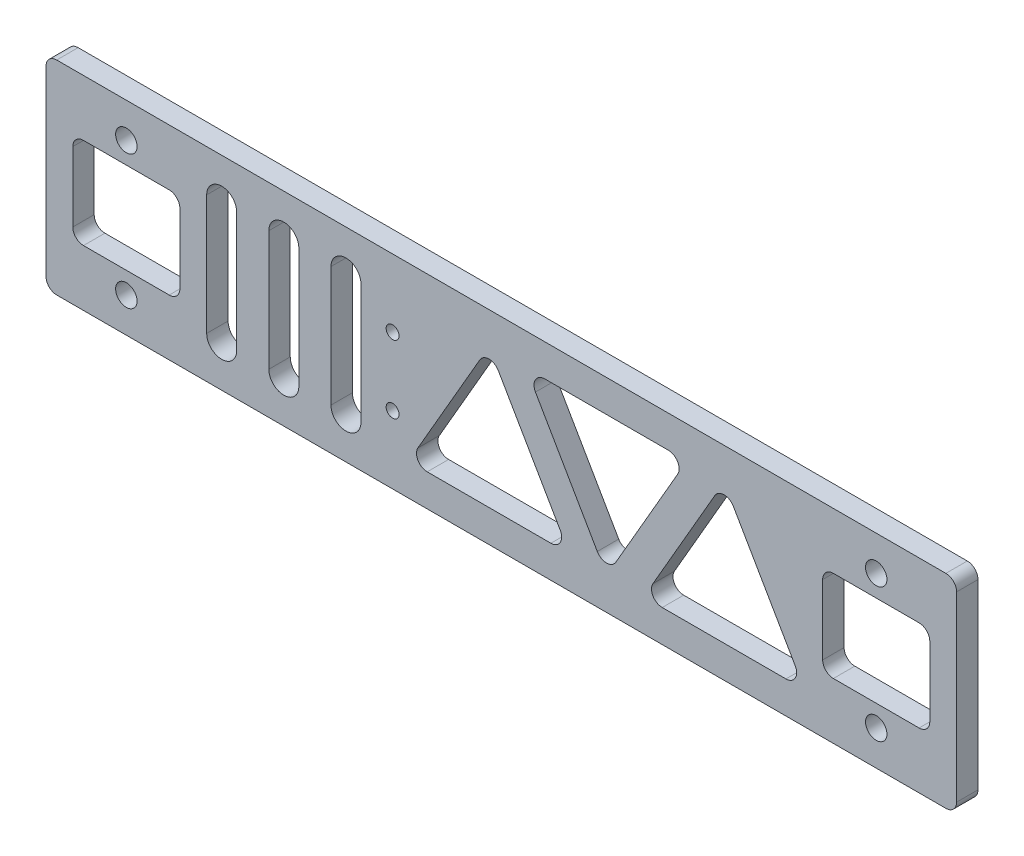
SolidWorks part; units mm, degrees
material "Thornel Mat VMA"
ref_plane "前视基准面" through (0, 0, 0) normal (0, 0, 1) x (1, 0, 0)
ref_plane "上视基准面" through (0, 0, 0) normal (0, 1, 0) x (1, 0, 0)
ref_plane "右视基准面" through (0, 0, 0) normal (1, 0, 0) x (0, 0, -1)
sketch "草图1" plane through (0, 0, 0) normal (0, 0, 1) x (1, 0, 0)
  line L1 (-85, -19) -> (85, -19)
  line L2 (-85, -19) -> (-85, 19)
  line L3 (-85, 19) -> (85, 19)
  line L4 (85, -19) -> (85, 19)
  line L5 (0, 19) -> (0, -19) construction
  line L6 (-85, 0) -> (85, 0) construction
  point P0 (0, 0)
  dimension "D1" = 170
  dimension "D2" = 38
extrude "凸台-拉伸1" add sketch "草图1" along normal blind 4
sketch "草图2" plane through (0, 0, 4) normal (0, 0, 1) x (1, 0, 0)
  line L0 (70, 19) -> (70, -19) construction
  line L1 (85, 19) -> (-85, 19) construction
  line L2 (-85, -19) -> (85, -19) construction
  line L3 (85, -19) -> (85, 19) construction
  line L4 (0, 0) -> (70, 0) construction
  circle A0 centre (70, 12.5) radius 2
  circle A1 centre (70, -12.5) radius 2
  dimension "D2" = 4
  dimension "D1" = 15
  dimension "D3" = 25
extrude "切除-拉伸1" cut sketch "草图2" against normal blind 4
mirror "镜向1" about plane through (0, 0, 0) normal (1, 0, 0) of "切除-拉伸1"
sketch "草图3" plane through (0, 0, 4) normal (0, 0, 1) x (1, 0, 0)
  line L0 (-17.295, -281.55) -> (-17.295, 41) construction
  line L1 (-17.295, -19) -> (-17.295, 19) construction
  line L2 (23.295, -281.55) -> (23.295, 41)
  line L3 (-23.295, 41) -> (-23.295, -281.55)
  line L5 (-23.295, 19) -> (-23.295, -19) construction
  line L6 (-23.295, 19) -> (-17.295, 19) construction
  line L7 (85, 19) -> (-85, 19) construction
  line L8 (-23.295, -19) -> (-17.295, -19) construction
  line L9 (-85, -19) -> (85, -19) construction
  line L10 (-20.295, 19) -> (-20.295, -19) construction
  line L11 (0, 0) -> (-20.295, 0) construction
  circle A0 centre (-20.295, 6.35) radius 1.2
  circle A1 centre (-20.295, -6.35) radius 1.2
  arc A2 (-23.295, -281.55) -> (23.295, -281.55) centre (0, -281.55) ccw
  arc A3 (23.295, 41) -> (-23.295, 41) centre (0, 41) ccw
  dimension "D2" = 2.4
  dimension "D3" = 12.7
  dimension "D1" = 0
extrude "切除-拉伸2" cut sketch "草图3" against normal blind 10
sketch "草图4" plane through (0, 0, 4) normal (0, 0, 1) x (1, 0, 0)
  line L0 (-70, 12.5) -> (-70, -12.5) construction
  line L1 (-85, 19) -> (-85, -19) construction
  line L2 (-80, -8.5) -> (-60, -8.5)
  line L3 (-80, -8.5) -> (-80, 8.5)
  line L4 (-80, 8.5) -> (-60, 8.5)
  line L5 (-60, -8.5) -> (-60, 8.5)
  line L6 (-70, 8.5) -> (-70, -8.5) construction
  line L7 (-80, 0) -> (-60, 0) construction
  circle A0 centre (-70, 12.5) radius 2 construction
  point P4 (-70, 0)
  dimension "D1" = 4
  dimension "D2" = 5
extrude "切除-拉伸3" cut sketch "草图4" against normal blind 10
mirror "镜向2" about plane through (0, 0, 0) normal (1, 0, 0) of "切除-拉伸3"
fillet "圆角1" radius 2 8 edges at (80, 8.5, 2) (80, -8.5, 2) (60, -8.5, 2) (60, 8.5, 2) (-80, 8.5, 2) (-60, 8.5, 2) (-80, -8.5, 2) (-60, -8.5, 2)
fillet "圆角2" radius 2 4 edges at (-85, -19, 2) (-85, 19, 2) (85, -19, 2) (85, 19, 2)
sketch "草图5" plane through (0, 0, 4) normal (0, 0, 1) x (1, 0, 0)
  line L0 (-2.2839, 13) -> (-17.295, -13)
  line L1 (-17.295, -13) -> (12.7272, -13)
  line L2 (12.7272, -13) -> (-2.2839, 13)
  line L3 (-83, -19) -> (83, -19) construction
  line L4 (83, 19) -> (-83, 19) construction
  line L5 (4.6443, 13) -> (19.6554, -13)
  line L6 (19.6554, -13) -> (34.6665, 13)
  line L7 (34.6665, 13) -> (4.6443, 13)
  line L8 (41.5947, 13) -> (26.5836, -13)
  line L9 (26.5836, -13) -> (56.6058, -13)
  line L10 (56.6058, -13) -> (41.5947, 13)
  circle A0 centre (-20.295, -6.35) radius 1.2 construction
  dimension "D1" = 6
  dimension "D2" = 6
  dimension "D3" = 6
  dimension "D4" = 6
  dimension "D5" = 3
extrude "切除-拉伸4" cut sketch "草图5" against normal blind 10
fillet "圆角3" radius 2 9 edges at (-2.2839, 13, 2) (56.6058, -13, 2) (26.5836, -13, 2) (41.5947, 13, 2) (34.6665, 13, 2) (19.6554, -13, 2) (4.6443, 13, 2) (12.7272, -13, 2) (-17.295, -13, 2)
sketch "草图6" plane through (0, 0, 4) normal (0, 0, 1) x (1, 0, 0)
  line L0 (-52.2, -11.2) -> (-52.2, 11.2) construction
  line L1 (-55, -11.2) -> (-55, 11.2)
  line L2 (-49.4, -11.2) -> (-49.4, 11.2)
  line L3 (-60, -6.5) -> (-60, 6.5) construction
  line L4 (-52.2, 0) -> (0, 0) construction
  line L8 (83, 19) -> (-83, 19) construction
  line L9 (-40.6, -11.2) -> (-40.6, 11.2) construction
  line L10 (-43.4, -11.2) -> (-43.4, 11.2)
  line L11 (-37.8, -11.2) -> (-37.8, 11.2)
  line L12 (-29, -11.2) -> (-29, 11.2) construction
  line L13 (-31.8, -11.2) -> (-31.8, 11.2)
  line L14 (-26.2, -11.2) -> (-26.2, 11.2)
  arc A0 (-55, -11.2) -> (-49.4, -11.2) centre (-52.2, -11.2) ccw
  arc A1 (-49.4, 11.2) -> (-55, 11.2) centre (-52.2, 11.2) ccw
  arc A2 (-43.4, -11.2) -> (-37.8, -11.2) centre (-40.6, -11.2) ccw
  arc A3 (-37.8, 11.2) -> (-43.4, 11.2) centre (-40.6, 11.2) ccw
  arc A4 (-31.8, -11.2) -> (-26.2, -11.2) centre (-29, -11.2) ccw
  arc A5 (-26.2, 11.2) -> (-31.8, 11.2) centre (-29, 11.2) ccw
  point P2 (-52.2, 0)
  point P17 (-40.6, 0)
  point P24 (-29, 0)
  dimension "D1" = 2.8
  dimension "D3" = 5
  dimension "D2" = 5
  dimension "D5" = 6
  dimension "D4" = 3
extrude "切除-拉伸5" cut sketch "草图6" against normal blind 10
equation "\"D4@草图5\"=\"D3@草图5\""
